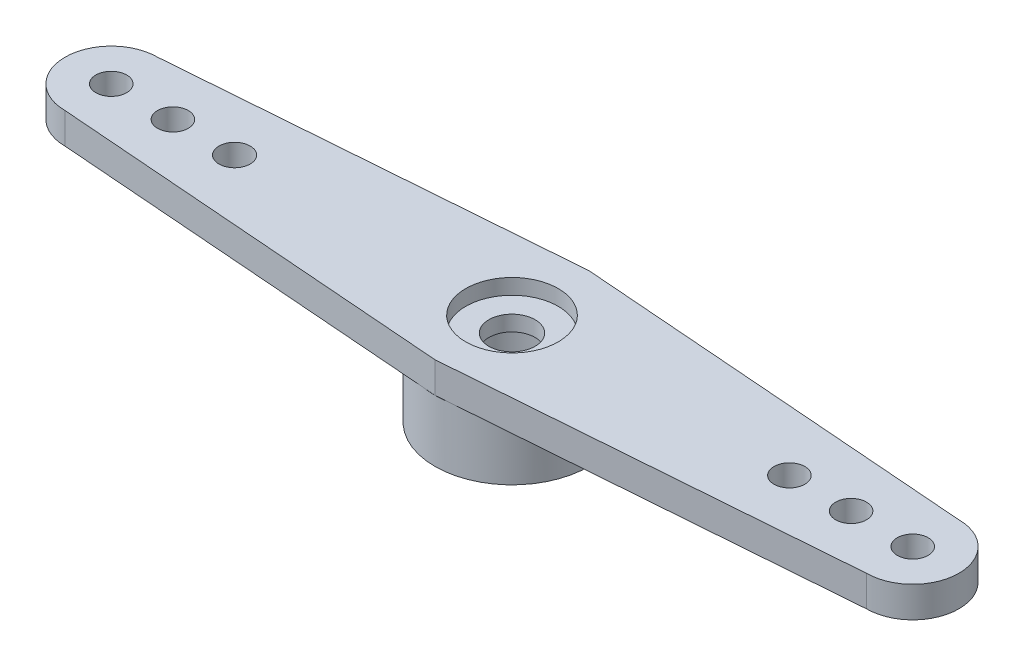
SolidWorks part; units mm, degrees
ref_plane "前视基准面" through (0, 0, 0) normal (0, 0, 1) x (1, 0, 0)
ref_plane "上视基准面" through (0, 0, 0) normal (0, 1, 0) x (1, 0, 0)
ref_plane "右视基准面" through (0, 0, 0) normal (1, 0, 0) x (0, 0, -1)
other "Configuration Table"
sketch "草图1" plane through (0, 0, 0) normal (0, 1, 0) x (1, 0, 0)
  line L0 (-13, 0) -> (13, 0) construction
  line L1 (0, 2.5) -> (13, 1.5)
  line L2 (13, -1.5) -> (0, -2.5)
  line L3 (0, 2.5) -> (-13, 1.5)
  line L4 (0, -2.5) -> (-13, -1.5)
  circle A0 centre (0, 0) radius 2.5
  circle A1 centre (13, 0) radius 1.5
  circle A2 centre (-13, 0) radius 1.5
  point P6 (0, 0)
  dimension "D1" = 5
  dimension "D3" = 3
  dimension "D4" = 3
  dimension "D2" = 26
extrude "凸台-拉伸2" add sketch "草图1" along normal blind 1
sketch "草图2" plane through (0, 0, 0) normal (0, 1, 0) x (1, 0, 0)
  circle A0 centre (0, 0) radius 2.5
  dimension "D1" = 5
extrude "凸台-拉伸3" add sketch "草图2" against normal blind 2
sketch "草图3" plane through (0, 0, 0) normal (0, 1, 0) x (1, 0, 0)
  circle A0 centre (0, 0) radius 1.5
  dimension "D1" = 3
extrude "切除-拉伸1" cut sketch "草图3" against normal blind 2
sketch "草图4" plane through (0, 0, 0) normal (0, 1, 0) x (1, 0, 0)
  circle A0 centre (0, 0) radius 0.75
  dimension "D1" = 1.5
extrude "切除-拉伸2" cut sketch "草图4" along normal blind 2
sketch "草图5" plane through (0, 0, 0) normal (0, 1, 0) x (1, 0, 0)
  circle A0 centre (0, 0) radius 1.5
  dimension "D1" = 3
extrude "切除-拉伸3" cut sketch "草图5" along normal blind 2 from offset 0.5
sketch "草图6" plane through (0, 0, 0) normal (0, 1, 0) x (1, 0, 0)
  line L0 (13, 0) -> (11, 0) construction
  line L1 (11, 0) -> (9, 0) construction
  line L2 (-13, 0) -> (-11, 0) construction
  line L4 (-11, 0) -> (-9, 0) construction
  circle A0 centre (13, 0) radius 0.5
  circle A1 centre (-13, 0) radius 0.5
  circle A2 centre (11, 0) radius 0.5
  circle A3 centre (9, 0) radius 0.5
  circle A4 centre (-11, 0) radius 0.5
  circle A5 centre (-9, 0) radius 0.5067
  point P15 (0, 0)
  dimension "D1" = 1
  dimension "D2" = 1
  dimension "D4" = 1
  dimension "D6" = 1
  dimension "D8" = 1
  dimension "D10" = 1.0134
  dimension "D3" = 2
  dimension "D5" = 2
  dimension "D7" = 2
  dimension "D9" = 2
extrude "切除-拉伸6" cut sketch "草图6" along normal blind 2 contours A5 | A4 | A1 | A0 | A2 | A3
